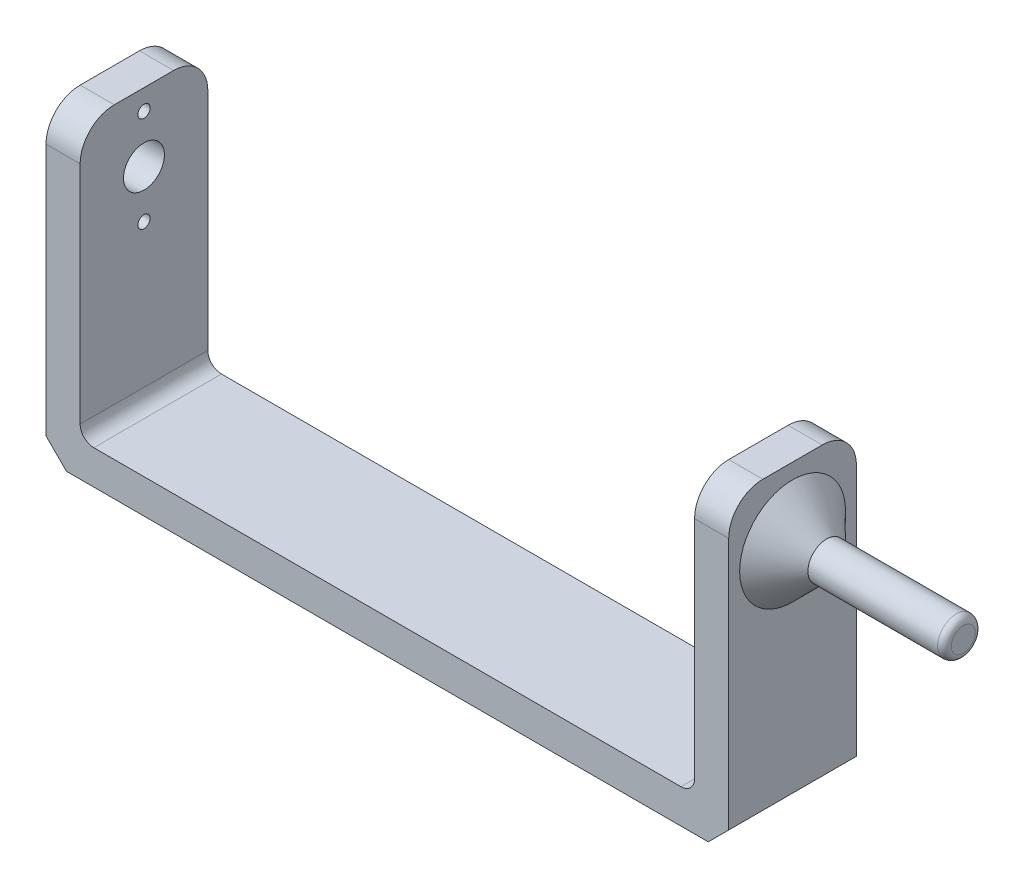
SolidWorks part; units mm, degrees
ref_plane "Front Plane" through (0, 0, 0) normal (0, 0, 1) x (1, 0, 0)
ref_plane "Top Plane" through (0, 0, 0) normal (0, 1, 0) x (1, 0, 0)
ref_plane "Right Plane" through (0, 0, 0) normal (1, 0, 0) x (0, 0, -1)
sketch "Sketch1" plane through (0, 0, 0) normal (0, 0, 1) x (1, 0, 0)
  line L1 (-45, -16.0352) -> (45, -16.0352)
  line L2 (-50, -16.0352) -> (-50, -21.0352)
  line L3 (-50, -21.0352) -> (50, -21.0352)
  line L4 (50, -16.0352) -> (50, -21.0352)
  line L5 (0, -18.5352) -> (50, -21.0352) construction
  line L6 (-50, -21.0352) -> (0, -18.5352) construction
  line L8 (-50, -16.0352) -> (-50, 23.9648)
  line L9 (-50, 23.9648) -> (-45, 23.9648)
  line L10 (-45, -16.0352) -> (-45, 23.9648)
  line L12 (50, -16.0352) -> (50, 23.9648)
  line L13 (50, 23.9648) -> (45, 23.9648)
  line L14 (45, -16.0352) -> (45, 23.9648)
  point P0 (0, -18.5352)
  dimension "D1" = 100
  dimension "D2" = 45
  dimension "D3" = 45
  dimension "D4" = 5
  dimension "D5" = 5
  dimension "D6" = 5
  dimension "D7" = 5
extrude "Boss-Extrude1" add sketch "Sketch1" along normal blind 18.7
fillet "Fillet1" radius 5 4 edges at (47.5, 23.9648, 0) (47.5, 23.9648, 18.7) (-47.5, 23.9648, 18.7) (-47.5, 23.9648, 0)
fillet "Fillet2" radius 2 2 edges at (45, -16.0352, 9.35) (-45, -16.0352, 9.35)
chamfer "Chamfer1" distance 3 angle 45 2 edges at (50, -21.0352, 9.35) (-50, -21.0352, 9.35)
sketch "Sketch2" plane through (-50, 0, 0) normal (-1, 0, 0) x (0, 0, 1)
  line L0 (13.7, 23.9648) -> (5, 23.9648) construction
  circle A0 centre (9.35, 13.9648) radius 3
  circle A1 centre (9.35, 20.9648) radius 0.9
  circle A2 centre (9.35, 6.9648) radius 0.9
  point P4 (9.35, 23.9648)
  dimension "D1" = 6
  dimension "D2" = 10
  dimension "D3" = 1.8
  dimension "D4" = 1.8
  dimension "D5" = 7
  dimension "D6" = 7
extrude "Cut-Extrude1" cut sketch "Sketch2" against normal blind 18.7
sketch "Sketch3" plane through (-50, 0, 0) normal (-1, 0, 0) x (0, 0, 1)
  circle A0 centre (9.35, 13.9648) radius 0.4144
extrude "Cut-Extrude2" cut sketch "Sketch3" against normal blind 118.7
sketch "Sketch4" plane through (50, 0, 0) normal (1, 0, 0) x (0, 0, -1)
  circle A0 centre (-9.35, 13.9648) radius 2.75
  dimension "D1" = 5.5
extrude "Boss-Extrude2" add sketch "Sketch4" along normal blind 25 and the other way blind 5
chamfer "Chamfer2" distance 5 angle 45 1 edges at (50, 13.9648, 12.1)
fillet "Fillet3" radius 1 1 edges at (75, 13.9648, 6.6)
